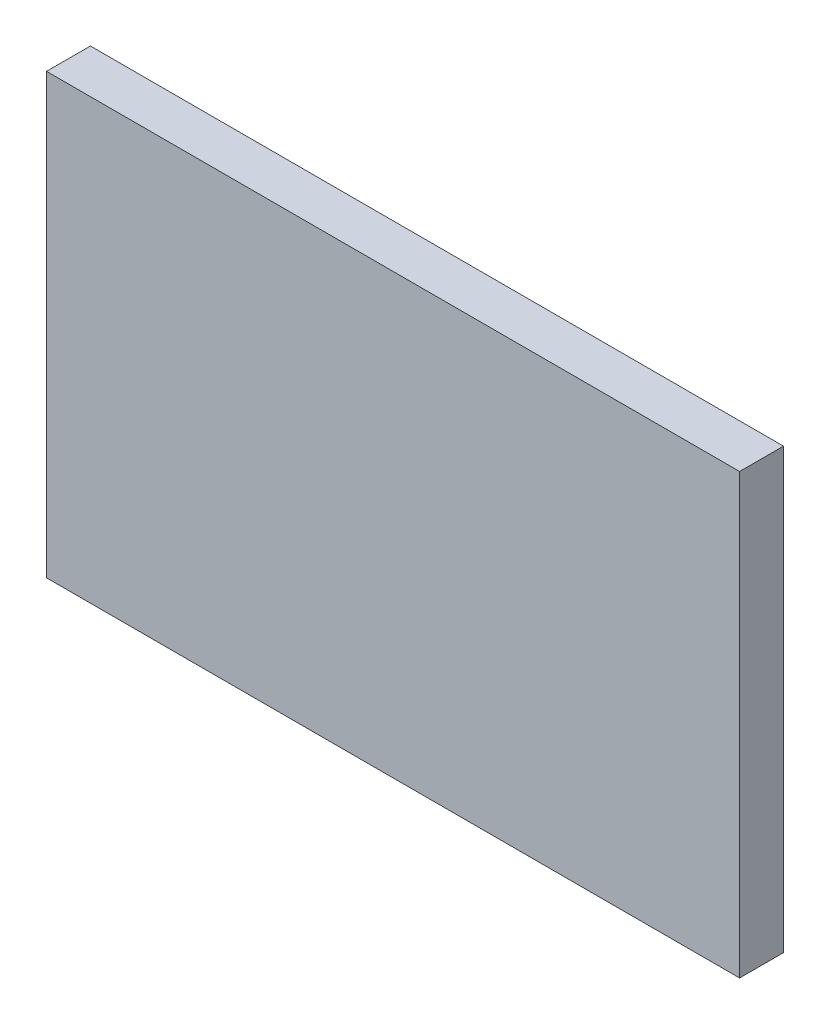
SolidWorks part; units mm, degrees
material "Простая углеродистая сталь"
ref_plane "Спереди" through (0, 0, 0) normal (0, 0, 1) x (1, 0, 0)
ref_plane "Сверху" through (0, 0, 0) normal (0, 1, 0) x (1, 0, 0)
ref_plane "Справа" through (0, 0, 0) normal (1, 0, 0) x (0, 0, -1)
sketch "Эскиз1" plane through (0, 0, 0) normal (0, 0, 1) x (1, 0, 0)
  line L1 (0, 0) -> (1580, 0)
  line L2 (0, 0) -> (0, -1000)
  line L3 (0, -1000) -> (1580, -1000)
  line L4 (1580, 0) -> (1580, -1000)
  line L5 (790, -1000) -> (790, 0) construction
  line L6 (0, -500) -> (1580, -500) construction
  point P88 (790, -500)
  dimension "D1" = 1580
  dimension "D2" = 1000
extrude "Бобышка-Вытянуть1" add sketch "Эскиз1" along normal blind 100
